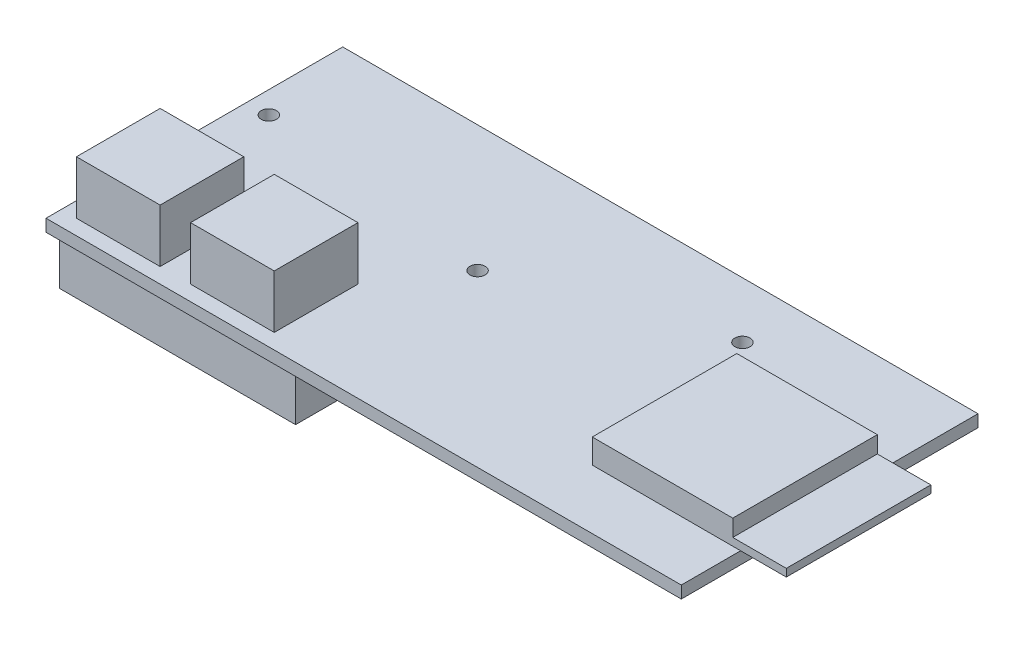
SolidWorks part; units mm, degrees
ref_plane "Front Plane" through (0, 0, 0) normal (0, 0, 1) x (1, 0, 0)
ref_plane "Top Plane" through (0, 0, 0) normal (0, 1, 0) x (1, 0, 0)
ref_plane "Right Plane" through (0, 0, 0) normal (1, 0, 0) x (0, 0, -1)
sketch "Sketch2" plane through (0, 0, 0) normal (0, 1, 0) x (1, 0, 0)
  line L1 (0, 0) -> (83.5, 0)
  line L2 (0, 0) -> (0, -39)
  line L3 (0, -39) -> (83.5, -39)
  line L4 (83.5, 0) -> (83.5, -39)
  dimension "D1" = 39
  dimension "D2" = 83.5
extrude "Boss-Extrude1" add sketch "Sketch2" along normal blind 1.6
sketch "Sketch3" plane through (0, 1.6, 0) normal (0, 1, 0) x (1, 0, 0)
  line L0 (83.5, -39) -> (83.5, 0) construction
  line L1 (64, -12.2) -> (89.5, -12.2)
  line L2 (64, -12.2) -> (64, -31.2)
  line L3 (64, -31.2) -> (89.5, -31.2)
  line L4 (89.5, -12.2) -> (89.5, -31.2)
  line L5 (0, -39) -> (83.5, -39) construction
  dimension "D1" = 19
  dimension "D2" = 6
  dimension "D3" = 7.8
  dimension "D4" = 25.5
extrude "Boss-Extrude2" add sketch "Sketch3" along normal blind 1
sketch "Sketch4" plane through (0, 2.6, 0) normal (0, 1, 0) x (1, 0, 0)
  line L0 (64, -31.2) -> (83.5, -31.2) construction
  line L1 (64, -12.2) -> (82.4667, -12.2)
  line L2 (64, -12.2) -> (64, -31.2)
  line L3 (64, -31.2) -> (82.4667, -31.2)
  line L4 (82.4667, -12.2) -> (82.4667, -31.2)
extrude "Boss-Extrude3" add sketch "Sketch4" along normal blind 2.2
sketch "Sketch5" plane through (0, 1.6, 0) normal (0, 1, 0) x (1, 0, 0)
  line L0 (83.5, 0) -> (0, 0) construction
  line L1 (83.5, -12.2) -> (83.5, 0) construction
  circle A0 centre (59.9, -7.36) radius 1
  circle A1 centre (34.32, -16.6) radius 1
  circle A2 centre (2.89, -12.6) radius 1
  dimension "D1" = 2
  dimension "D2" = 2
  dimension "D3" = 2
  dimension "D4" = 7.36
  dimension "D5" = 23.6
  dimension "D6" = 16.6
  dimension "D7" = 49.18
  dimension "D8" = 12.6
  dimension "D9" = 80.61
extrude "Cut-Extrude1" cut sketch "Sketch5" against normal blind 2.2
sketch "Sketch6" plane through (0, 1.6, 0) normal (0, 1, 0) x (1, 0, 0)
  line L0 (0, -39) -> (83.5, -39) construction
  line L1 (2, -26) -> (13, -26)
  line L2 (2, -26) -> (2, -37)
  line L3 (2, -37) -> (13, -37)
  line L4 (13, -26) -> (13, -37)
  line L5 (17, -26) -> (28, -26)
  line L6 (17, -26) -> (17, -37)
  line L7 (17, -37) -> (28, -37)
  line L8 (28, -26) -> (28, -37)
  line L9 (0, 0) -> (0, -39) construction
  dimension "D1" = 11
  dimension "D2" = 11
  dimension "D3" = 2
  dimension "D4" = 2
  dimension "D5" = 11
  dimension "D6" = 11
  dimension "D7" = 2
  dimension "D8" = 26
extrude "Boss-Extrude4" add sketch "Sketch6" along normal blind 7
sketch "Sketch7" plane through (0, 0, 0) normal (0, -1, 0) x (-1, 0, 0)
  line L0 (0, -39) -> (-83.5, -39) construction
  line L1 (0.2, -37) -> (-30.8, -37)
  line L2 (0.2, -37) -> (0.2, -22)
  line L3 (0.2, -22) -> (-30.8, -22)
  line L4 (-30.8, -37) -> (-30.8, -22)
  line L5 (0, 0) -> (0, -39) construction
  dimension "D1" = 31
  dimension "D2" = 15
  dimension "D3" = 2
  dimension "D4" = 0.2
extrude "Boss-Extrude5" add sketch "Sketch7" along normal blind 7.5
equation "\"D4@Sketch5\"=6.36+1"
